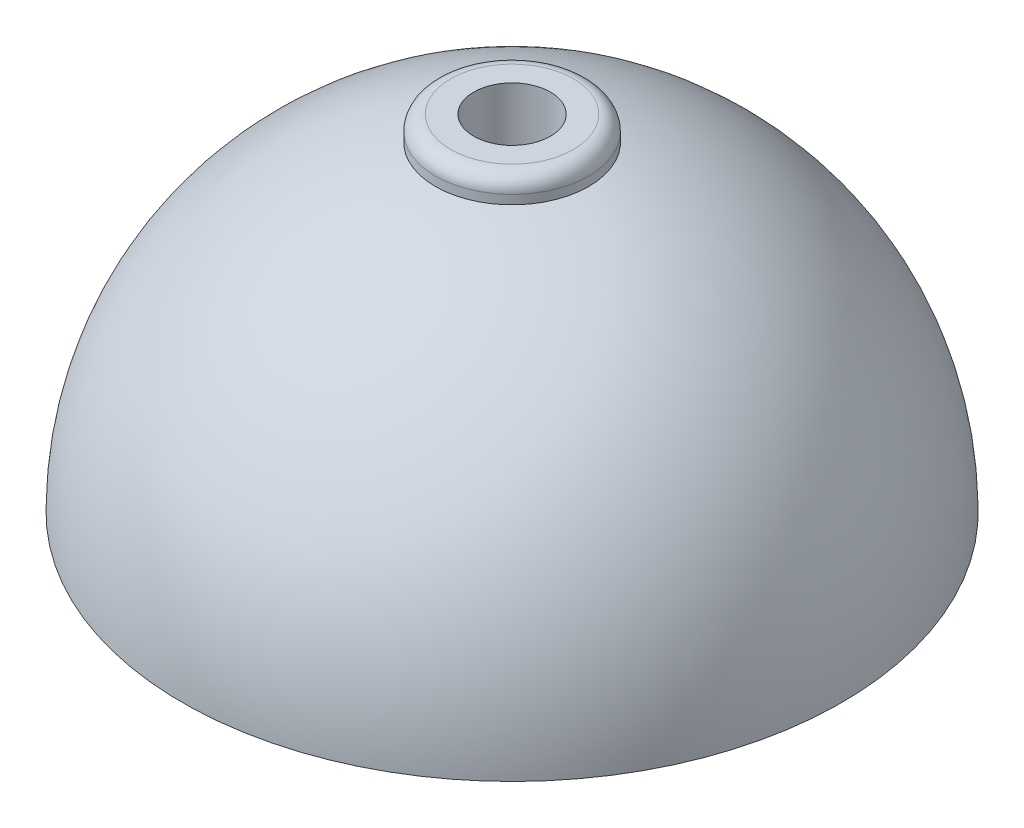
SolidWorks part; units mm, degrees
ref_plane "Front Plane" through (0, 0, 0) normal (0, 0, 1) x (1, 0, 0)
ref_plane "Top Plane" through (0, 0, 0) normal (0, 1, 0) x (1, 0, 0)
ref_plane "Right Plane" through (0, 0, 0) normal (1, 0, 0) x (0, 0, -1)
sketch "Sketch1" plane through (0, 0, 0) normal (0, 0, 1) x (1, 0, 0)
  line L0 (0, 0) -> (0, 18532.3191) construction
  line L1 (0, 0) -> (21.5, 0)
  line L2 (0, 0) -> (0, 21.5)
  arc A0 (21.5, 0) -> (0, 21.5) centre (0, 0) ccw
  dimension "D1" = 43
revolve "Revolve1" add sketch "Sketch1" angle 360 about L0
shell "Shell1" thickness 2
ref_plane "Plane1" through (0, 21.5, 0) normal (0, 1, 0) x (1, 0, 0)
sketch "Sketch4" plane through (0, 21.5, 0) normal (0, 1, 0) x (1, 0, 0)
  circle A0 centre (0, 0) radius 5
  dimension "D1" = 10
extrude "Boss-Extrude6" add sketch "Sketch4" along normal blind 1 and the other way blind 15
sketch "Sketch2" plane through (0, 0, 0) normal (0, 1, 0) x (1, 0, 0)
  circle A0 centre (0, 0) radius 2.5
  dimension "D1" = 5
extrude "Cut-Extrude3" cut sketch "Sketch2" along normal through all
fillet "Fillet1" radius 1 1 edges at (0, 22.5, 5)
